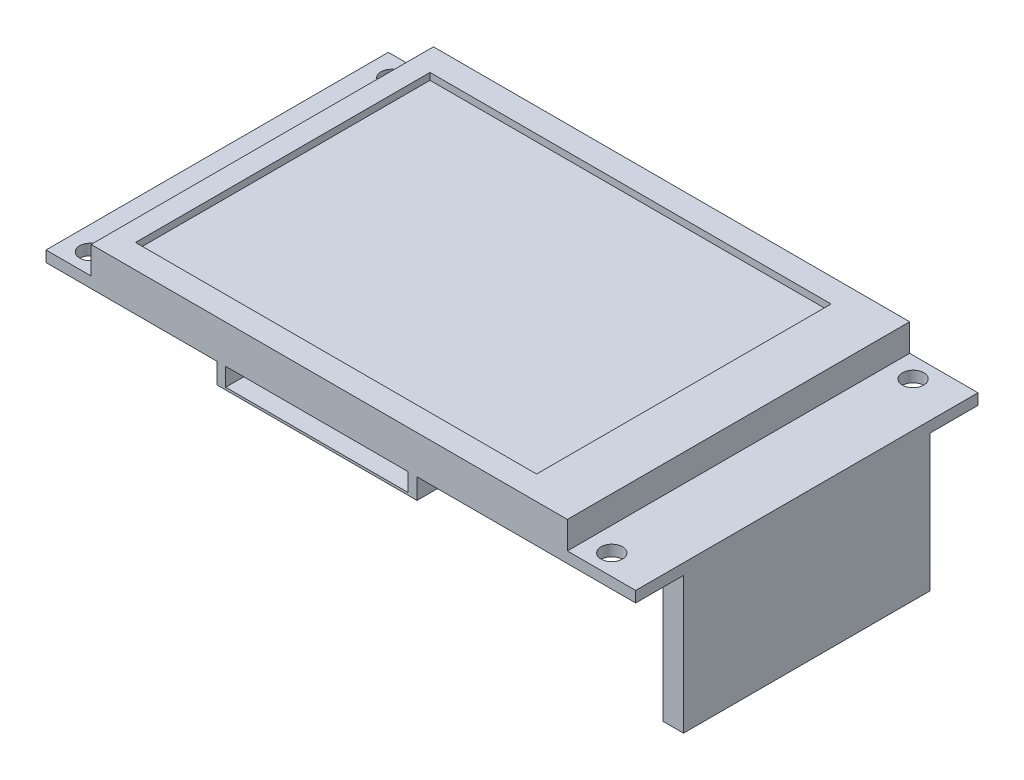
SolidWorks part; units mm, degrees
ref_plane "Front Plane" through (0, 0, 0) normal (0, 0, 1) x (1, 0, 0)
ref_plane "Top Plane" through (0, 0, 0) normal (0, 1, 0) x (1, 0, 0)
ref_plane "Right Plane" through (0, 0, 0) normal (1, 0, 0) x (0, 0, -1)
sketch "Sketch1" plane through (0, 0, 0) normal (0, 1, 0) x (1, 0, 0)
  line L1 (-43.15, -25.05) -> (43.15, -25.05)
  line L2 (-43.15, -25.05) -> (-43.15, 25.05)
  line L3 (-43.15, 25.05) -> (43.15, 25.05)
  line L4 (43.15, -25.05) -> (43.15, 25.05)
  line L5 (-43.15, -25.05) -> (43.15, 25.05) construction
  line L6 (-43.15, 25.05) -> (43.15, -25.05) construction
  point P0 (0, 0)
  point P12 (-39.7553, 21.3796)
  point P13 (-40.15, 22.05)
  dimension "D1" = 86.3
  dimension "D2" = 50.1
extrude "CIRCUIT" add sketch "Sketch1" along normal blind 1.6
sketch "Sketch2" plane through (0, 1.6, 0) normal (0, 1, 0) x (1, 0, 0)
  line L0 (-43.15, 25.05) -> (-43.15, -25.05) construction
  line L1 (43.15, 25.05) -> (-43.15, 25.05) construction
  line L2 (-43.15, -25.05) -> (43.15, -25.05) construction
  line L3 (43.15, -25.05) -> (43.15, 25.05) construction
  circle A0 centre (-39.65, 22.05) radius 1.57
  circle A1 centre (-39.65, -22.05) radius 1.57
  circle A2 centre (36.65, 22.05) radius 1.57
  circle A3 centre (36.65, -22.05) radius 1.57
  point P14 (0, 0)
  point P15 (0, 0)
  point P16 (0, 0)
  point P17 (0, 0)
  point P18 (0, 0)
  dimension "D1" = 3.14
  dimension "D2" = 3.5
  dimension "D3" = 3
  dimension "D4" = 6.5
  dimension "D5" = 3
extrude "SCREW_HOLES" cut sketch "Sketch2" against normal through all
sketch "Sketch3" plane through (0, 1.6, 0) normal (0, 1, 0) x (1, 0, 0)
  line L0 (43.15, 25.05) -> (-43.15, 25.05) construction
  line L1 (-36.55, 25.05) -> (33.15, 25.05)
  line L2 (-36.55, 25.05) -> (-36.55, -25.05)
  line L3 (-36.55, -25.05) -> (33.15, -25.05)
  line L4 (33.15, 25.05) -> (33.15, -25.05)
  line L5 (-43.15, -25.05) -> (43.15, -25.05) construction
  line L6 (-43.15, 25.05) -> (-43.15, -25.05) construction
  line L7 (43.15, -25.05) -> (43.15, 25.05) construction
  dimension "D1" = 6.6
  dimension "D2" = 10
extrude "LCD" add sketch "Sketch3" along normal blind 4
sketch "Sketch4" plane through (0, 0, 0) normal (0, -1, 0) x (1, 0, 0)
  line L0 (43.15, 25.05) -> (43.15, -25.05) construction
  line L1 (40.15, 18.05) -> (43.15, 18.05)
  line L2 (40.15, 18.05) -> (40.15, -18.05)
  line L3 (40.15, -18.05) -> (43.15, -18.05)
  line L4 (43.15, 18.05) -> (43.15, -18.05)
  line L5 (-43.15, 25.05) -> (43.15, 25.05) construction
  line L6 (43.15, -25.05) -> (-43.15, -25.05) construction
  dimension "D1" = 7
  dimension "D2" = 7
  dimension "D3" = 3
extrude "PINS" add sketch "Sketch4" along normal blind 20
sketch "Sketch6" plane through (0, 0, 0) normal (0, -1, 0) x (1, 0, 0)
  line L0 (-43.15, 25.05) -> (43.15, 25.05) construction
  line L1 (-18.15, 25.05) -> (11.15, 25.05)
  line L2 (-18.15, 25.05) -> (-18.15, 5.05)
  line L3 (-18.15, 5.05) -> (11.15, 5.05)
  line L4 (11.15, 25.05) -> (11.15, 5.05)
  line L5 (43.15, 25.05) -> (43.15, 18.05) construction
  line L6 (-43.15, -25.05) -> (-43.15, 25.05) construction
  dimension "D1" = 32
  dimension "D2" = 25
  dimension "D3" = 20
extrude "SD_SLOT" add sketch "Sketch6" along normal blind 3
sketch "Sketch8" plane through (0, 0, 25.05) normal (0, 0, 1) x (1, 0, 0)
  line L0 (-43.15, 0) -> (-18.15, 0) construction
  line L1 (-16.85, 0) -> (9.85, 0)
  line L2 (-16.85, 0) -> (-16.85, -2.65)
  line L3 (-16.85, -2.65) -> (9.85, -2.65)
  line L4 (9.85, 0) -> (9.85, -2.65)
  line L5 (11.15, -3) -> (-18.15, -3) construction
  line L6 (-18.15, -3) -> (-18.15, 0) construction
  line L7 (11.15, -3) -> (11.15, 0) construction
  dimension "D1" = 0.35
  dimension "D2" = 1.3
  dimension "D3" = 1.3
extrude "Cut-Extrude2" cut sketch "Sketch8" against normal blind 5
sketch "Sketch9" plane through (0, 5.6, 0) normal (0, 1, 0) x (1, 0, 0)
  line L0 (33.15, -25.05) -> (33.15, 25.05) construction
  line L1 (-36.55, 25.05) -> (-36.55, -25.05) construction
  line L2 (33.15, 25.05) -> (-36.55, 25.05) construction
  line L3 (-36.55, -25.05) -> (33.15, -25.05) construction
  line L5 (-33.55, 21.55) -> (25.15, 21.55)
  line L6 (-33.55, 21.55) -> (-33.55, -21.55)
  line L7 (-33.55, -21.55) -> (25.15, -21.55)
  line L8 (25.15, 21.55) -> (25.15, -21.55)
  dimension "D1" = 8
  dimension "D2" = 3
  dimension "D3" = 3.5
  dimension "D4" = 3.5
extrude "Cut-Extrude3" cut sketch "Sketch9" against normal blind 1
